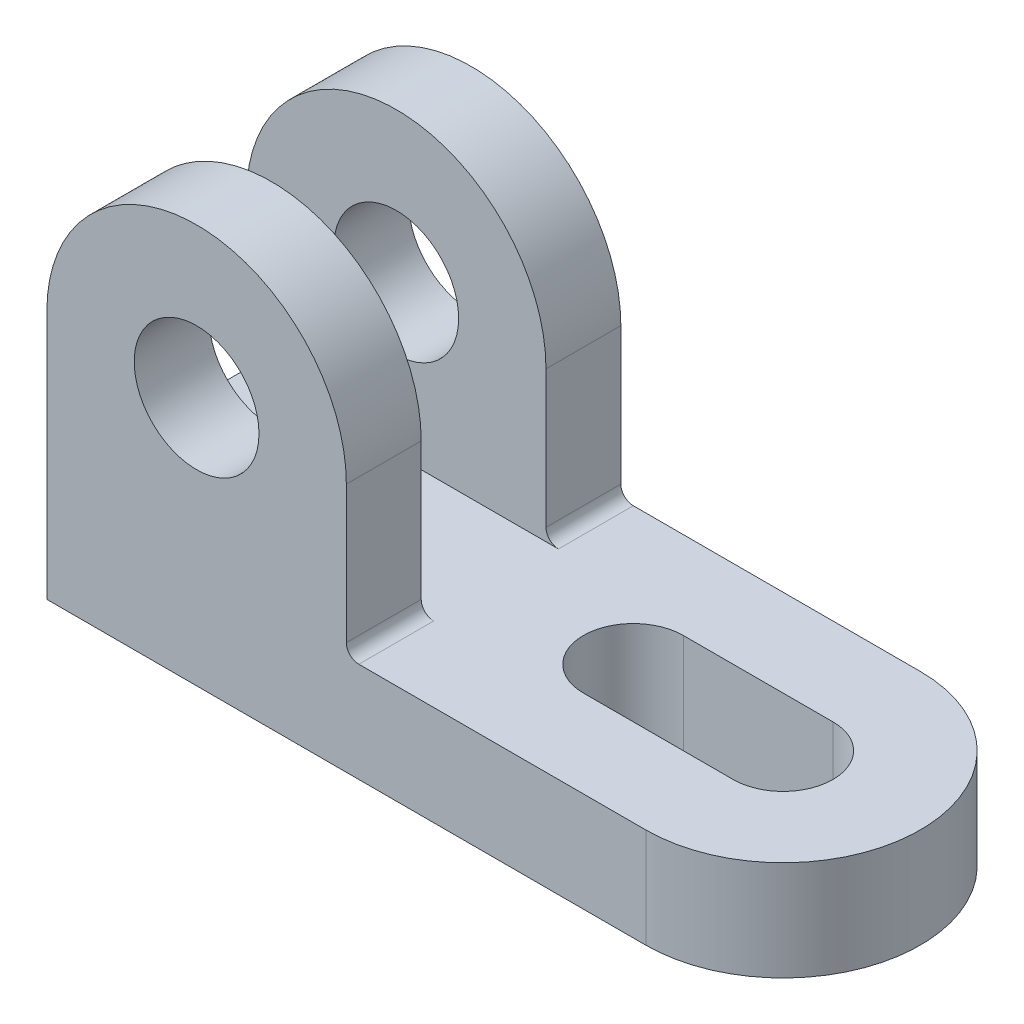
SolidWorks part; units mm, degrees
ref_plane "Front Plane" through (0, 0, 0) normal (0, 0, 1) x (1, 0, 0)
ref_plane "Top Plane" through (0, 0, 0) normal (0, 1, 0) x (1, 0, 0)
ref_plane "Right Plane" through (0, 0, 0) normal (1, 0, 0) x (0, 0, -1)
sketch "Sketch1" plane through (0, 0, 0) normal (0, 1, 0) x (1, 0, 0)
  line L1 (-59, 22) -> (59, 22)
  line L2 (-59, 22) -> (-59, -22)
  line L3 (-59, -22) -> (59, -22)
  line L4 (59, 22) -> (59, -22)
  line L5 (-59, 22) -> (59, -22) construction
  line L6 (-59, -22) -> (59, 22) construction
  circle A0 centre (37, 0) radius 22
  point P0 (0, 0)
  dimension "D1" = 118
  dimension "D2" = 44
extrude "Boss-Extrude2" add sketch "Sketch1" along normal blind 16 contours A0 L1 L2 L3 | A0
sketch "Sketch2" plane through (0, 0, 22) normal (0, 0, 1) x (1, 0, 0)
  line L0 (-59, 0) -> (37, 0) construction
  line L1 (-59, 16) -> (-11, 16)
  line L2 (-59, 16) -> (-59, 40)
  line L3 (-59, 40) -> (-11, 40)
  line L4 (-11, 16) -> (-11, 40)
  circle A0 centre (-35, 40) radius 24
  circle A1 centre (-35, 40) radius 10
  line M7 (37, 16) -> (-59, 16)
  dimension "D3" = 20
  dimension "D1" = 48
  dimension "D2" = 40
extrude "Boss-Extrude3" add sketch "Sketch2" against normal blind 12 contours A0 L4 M7 | A0 L2 L1 | A1 L3 A0 | A1 L3 A0
mirror "Mirror1" about plane through (0, 0, 0) normal (0, 0, 1) of "Boss-Extrude3"
sketch "Sketch3" plane through (0, 16, 0) normal (0, 1, 0) x (1, 0, 0)
  line L0 (13, 0) -> (37, 0) construction
  line L1 (13, 8) -> (37, 8)
  line L2 (13, -8) -> (37, -8)
  line L3 (-59, 10) -> (-59, -10) construction
  arc A0 (13, 8) -> (13, -8) centre (13, 0) ccw
  arc A1 (37, -8) -> (37, 8) centre (37, 0) ccw
  point P3 (25, 0)
  dimension "D1" = 16
  dimension "D2" = 24
  dimension "D3" = 72
extrude "Cut-Extrude1" cut sketch "Sketch3" against normal blind 16
fillet "Fillet1" radius 2 2 edges at (-11, 16, -16) (-11, 16, 16)
